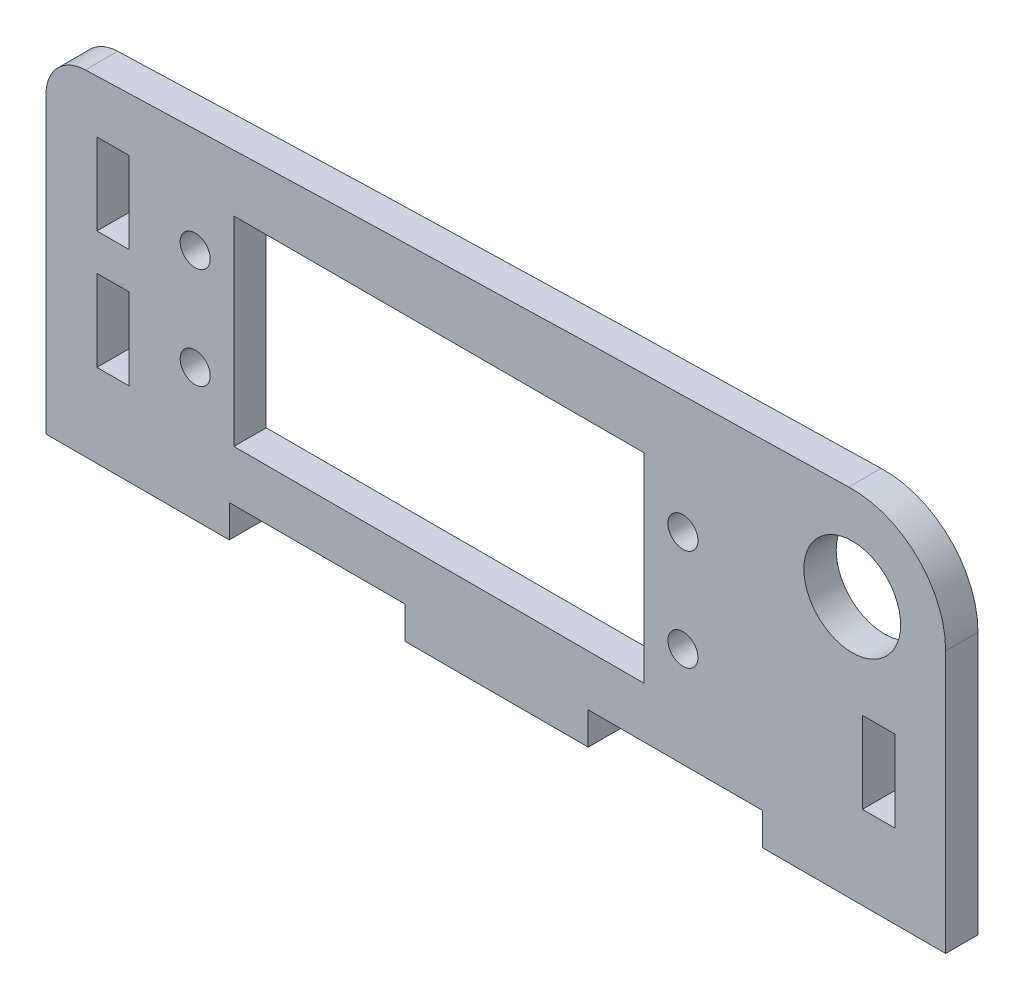
SolidWorks part; units mm, degrees
ref_plane "Front Plane" through (0, 0, 0) normal (0, 0, 1) x (1, 0, 0)
ref_plane "Top Plane" through (0, 0, 0) normal (0, 1, 0) x (1, 0, 0)
ref_plane "Right Plane" through (0, 0, 0) normal (1, 0, 0) x (0, 0, -1)
sketch "Sketch1" plane through (0, 0, 0) normal (0, 0, 1) x (1, 0, 0)
  line L1 (-26.416, -9.8) -> (26.416, -9.8)
  line L2 (-26.416, -9.8) -> (-26.416, 9.8)
  line L3 (-26.416, 9.8) -> (26.416, 9.8)
  line L4 (26.416, -9.8) -> (26.416, 9.8)
  line L5 (-26.416, -9.8) -> (26.416, 9.8) construction
  line L6 (-26.416, 9.8) -> (26.416, -9.8) construction
  line L7 (-20.15, -9.8) -> (20.15, -9.8)
  line L8 (-20.15, -9.8) -> (-20.15, 9.8)
  line L9 (-20.15, 9.8) -> (20.15, 9.8)
  line L10 (20.15, -9.8) -> (20.15, 9.8)
  line L11 (-20.15, -9.8) -> (20.15, 9.8) construction
  line L12 (-20.15, 9.8) -> (20.15, -9.8) construction
  line L13 (-26.416, 9.8) -> (26.416, 9.8)
  line L14 (-26.416, 9.8) -> (-26.416, 14.8)
  line L15 (-26.416, 14.8) -> (26.416, 14.8)
  line L16 (26.416, 9.8) -> (26.416, 14.8)
  line L17 (26.416, -9.8) -> (-26.416, -9.8)
  line L18 (26.416, -9.8) -> (26.416, -14.8)
  line L19 (26.416, -14.8) -> (-26.416, -14.8)
  line L20 (-26.416, -9.8) -> (-26.416, -14.8)
  circle A0 centre (-23.95, -4.974) radius 1.475
  circle A1 centre (-23.95, 4.974) radius 1.475
  circle A2 centre (23.95, 4.974) radius 1.475
  circle A3 centre (23.95, -4.974) radius 1.475
  point P0 (0, 0)
  point P14 (0, 0)
  dimension "D1" = 2.95
  dimension "D2" = 2.95
  dimension "D3" = 2.95
  dimension "D4" = 2.95
  dimension "D7" = 4.826
  dimension "D8" = 3.8
  dimension "D9" = 3.8
  dimension "D10" = 4.826
  dimension "D11" = 4.826
  dimension "D12" = 4.826
  dimension "D13" = 3.8
  dimension "D5" = 19.6
  dimension "D6" = 52.832
  dimension "D15" = 40.3
  dimension "D16" = 5
  dimension "D17" = 5
  dimension "3.9" = 3.8
extrude "Boss-Extrude2" add sketch "Sketch1" along normal blind 3.175 contours L1 L8 L3 L2 A1 A0 | L10 L1 L4 L3 A3 A2 | L14 L13 L16 L15 | L18 L17 L20 L19
sketch "Sketch3" plane through (0, 0, 3.175) normal (0, 0, 1) x (1, 0, 0)
  line L0 (26.416, -14.8) -> (56.416, -14.8)
  line L6 (26.416, 14.8) -> (56.416, 14.8)
  line L7 (26.416, 14.8) -> (26.416, -14.906)
  line L8 (26.416, -14.906) -> (56.416, -14.906)
  line L9 (56.416, 14.8) -> (56.416, -14.906)
  line M3 (26.416, -14.8) -> (26.416, 14.8)
  dimension "D2" = 30
extrude "Boss-Extrude3" add sketch "Sketch3" against normal up to surface (3.175 mm away) contours L9 L6 L0 M3 up to face at (0, 0, 0)
sketch "Sketch4" plane through (0, 0, 0) normal (0, 0, -1) x (-1, 0, 0)
  line L3 (-56.416, 14.8) -> (-56.416, -14.8) construction
  line L4 (-56.416, -14.8) -> (26.416, -14.8) construction
  circle A0 centre (-40.576, 7.77) radius 4.75
  dimension "D1" = 15.84
  dimension "D2" = 22.57
  dimension "D3" = 9.5
extrude "Cut-Extrude1" cut sketch "Sketch4" against normal blind 10 contours A0
sketch "Sketch22" plane through (0, 0, 0) normal (0, 0, -1) x (-1, 0, 0)
  line L0 (-52.3294, 14.8) -> (-30.0917, 14.8)
  line L1 (26.416, 14.8) -> (-56.416, 14.8) construction
  circle A0 centre (-40.576, 7.77) radius 9.175
  dimension "D1" = 18.35
extrude "Boss-Extrude14" add sketch "Sketch22" against normal up to surface (3.175 mm away) contours L0 A0
sketch "Sketch23" plane through (0, 0, 0) normal (0, 0, -1) x (-1, 0, 0)
  line L0 (-49.751, 7.77) -> (-49.751, -14.8)
  line L1 (-56.416, -14.8) -> (26.416, -14.8) construction
  circle A0 centre (-40.576, 7.77) radius 9.175
  line M4 (-46.4717, 14.8) -> (-56.416, 14.8)
  line M5 (-56.416, 14.8) -> (-56.416, -14.8)
  line M6 (-56.416, -14.8) -> (26.416, -14.8)
extrude "Cut-Extrude8" cut sketch "Sketch23" against normal blind 10 contours A0 L0 M4 M5 M6
sketch "Sketch24" plane through (0, 0, 0) normal (0, 0, -1) x (-1, 0, 0)
  line L0 (25.425, 4.974) -> (25.425, 17.1862)
  line L1 (21.4452, -14.8) -> (27.751, -14.8)
  line L2 (-49.751, -14.8) -> (26.416, -14.8) construction
  line L3 (26.416, 14.8) -> (-34.6803, 14.8) construction
  line L4 (25.425, 14.8) -> (30.425, 14.8)
  line L5 (25.425, 14.8) -> (25.425, -14.8)
  line L6 (25.425, -14.8) -> (30.425, -14.8)
  line L7 (30.425, 14.8) -> (30.425, -14.8)
  circle A0 centre (23.95, 4.974) radius 1.475 construction
  line M14 (26.416, -14.8) -> (26.416, 14.8)
  dimension "D1" = 5
extrude "Boss-Extrude15" add sketch "Sketch24" against normal up to surface (3.175 mm away) contours L7 L4 L1 L6 M14 up to face at (45.326, 7.77, 3.175)
sketch "Sketch25" plane through (0, 0, 0) normal (0, 0, -1) x (-1, 0, 0)
  line L0 (30.425, 14.8) -> (30.425, -14.8) construction
  line L1 (30.425, 9.8) -> (33.6, 9.8)
  line L2 (30.425, 9.8) -> (30.425, 1.8)
  line L3 (30.425, 1.8) -> (33.6, 1.8)
  line L4 (33.6, 9.8) -> (33.6, 1.8)
  line L5 (28.9462, -14.8) -> (31.8791, -14.8)
  line L6 (30.425, -1.8) -> (33.6, -1.8)
  line L7 (30.425, -1.8) -> (30.425, -9.8)
  line L8 (30.425, -9.8) -> (33.6, -9.8)
  line L9 (33.6, -1.8) -> (33.6, -9.8)
  line L10 (-49.751, -14.8) -> (30.425, -14.8) construction
  line L12 (30.425, 14.8) -> (38.6, 14.8)
  line L13 (30.425, 14.8) -> (30.425, -14.8)
  line L14 (30.425, -14.8) -> (38.6, -14.8)
  line L15 (38.6, 14.8) -> (38.6, -14.8)
  line M23 (30.425, -14.8) -> (30.425, 14.8)
  dimension "D1" = 3.175
  dimension "D2" = 3.175
  dimension "D3" = 8
  dimension "D4" = 8
  dimension "D5" = 5
  dimension "D6" = 0
  dimension "D7" = 8.175
  dimension "D8" = 5
extrude "Boss-Extrude16" add sketch "Sketch25" against normal up to surface (3.175 mm away) contours L15 L12 L1 L4 L3 L6 L9 L8 L5 L14 M23 up to face at (45.326, 7.77, 3.175)
sketch "Sketch26" plane through (0, 0, 0) normal (0, 0, -1) x (-1, 0, 0)
  line L0 (-34.6803, 14.8) -> (38.6, 14.8)
  arc A0 (-40.576, 16.945) -> (38.6, 14.8) centre (-135.9707, -4966.5923) cw
  arc A1 (-34.6803, 14.8) -> (-49.751, 7.77) centre (-40.576, 7.77) ccw construction
  circle A2 centre (-40.576, 7.77) radius 9.175
  arc M18 (-34.6803, 14.8) -> (-49.751, 7.77) centre (-40.576, 7.77) ccw
  line M22 (38.6, 14.8) -> (-34.6803, 14.8)
extrude "Boss-Extrude17" add sketch "Sketch26" against normal up to surface (3.175 mm away) contours A0 M18 M22 up to face at (-32.0125, 5.8, 3.175)
fillet "Fillet5" radius 4 1 edges at (-38.6, 14.8, 1.5875)
sketch "Sketch27" plane through (0, 0, 0) normal (0, 0, -1) x (-1, 0, 0)
  line L0 (-49.751, -14.8) -> (38.6, -14.8) construction
  line L1 (-44.751, -9.8) -> (-41.576, -9.8)
  line L2 (-44.751, -9.8) -> (-44.751, -1.8)
  line L3 (-44.751, -1.8) -> (-41.576, -1.8)
  line L4 (-41.576, -9.8) -> (-41.576, -1.8)
  line L5 (-49.751, 7.77) -> (-49.751, -14.8) construction
  dimension "D1" = 3.175
  dimension "D2" = 8
  dimension "D3" = 5
  dimension "D4" = 5
extrude "Cut-Extrude9" cut sketch "Sketch27" against normal blind 10
sketch "Sketch28" plane through (0, 0, 0) normal (0, 0, -1) x (-1, 0, 0)
  line L0 (-49.751, -14.8) -> (38.6, -14.8) construction
  line L1 (-49.751, -14.8) -> (-31.751, -14.8)
  line L2 (-49.751, -14.8) -> (-49.751, -17.975)
  line L3 (-49.751, -17.975) -> (-31.751, -17.975)
  line L4 (-31.751, -14.8) -> (-31.751, -17.975)
  line L5 (-14.65, -14.8) -> (3.35, -14.8)
  line L6 (-14.65, -14.8) -> (-14.65, -17.975)
  line L7 (-14.65, -17.975) -> (3.35, -17.975)
  line L8 (3.35, -14.8) -> (3.35, -17.975)
  line L9 (38.6, 10.9362) -> (38.6, -14.8) construction
  line L10 (20.6, -14.8) -> (38.6, -14.8)
  line L11 (20.6, -14.8) -> (20.6, -17.975)
  line L12 (20.6, -17.975) -> (38.6, -17.975)
  line L13 (38.6, -14.8) -> (38.6, -17.975)
  dimension "D1" = 3.175
  dimension "D2" = 3.175
  dimension "D3" = 3.175
  dimension "D4" = 18
  dimension "D5" = 18
  dimension "D6" = 18
  dimension "D7" = 0
  dimension "D8" = 17.25
extrude "Boss-Extrude18" add sketch "Sketch28" against normal up to surface (3.175 mm away) contours L2 L1 L4 L3 | L6 L5 L8 L7 | L11 L10 L13 L12 up to face at (43.1635, -5.8, 3.175)
